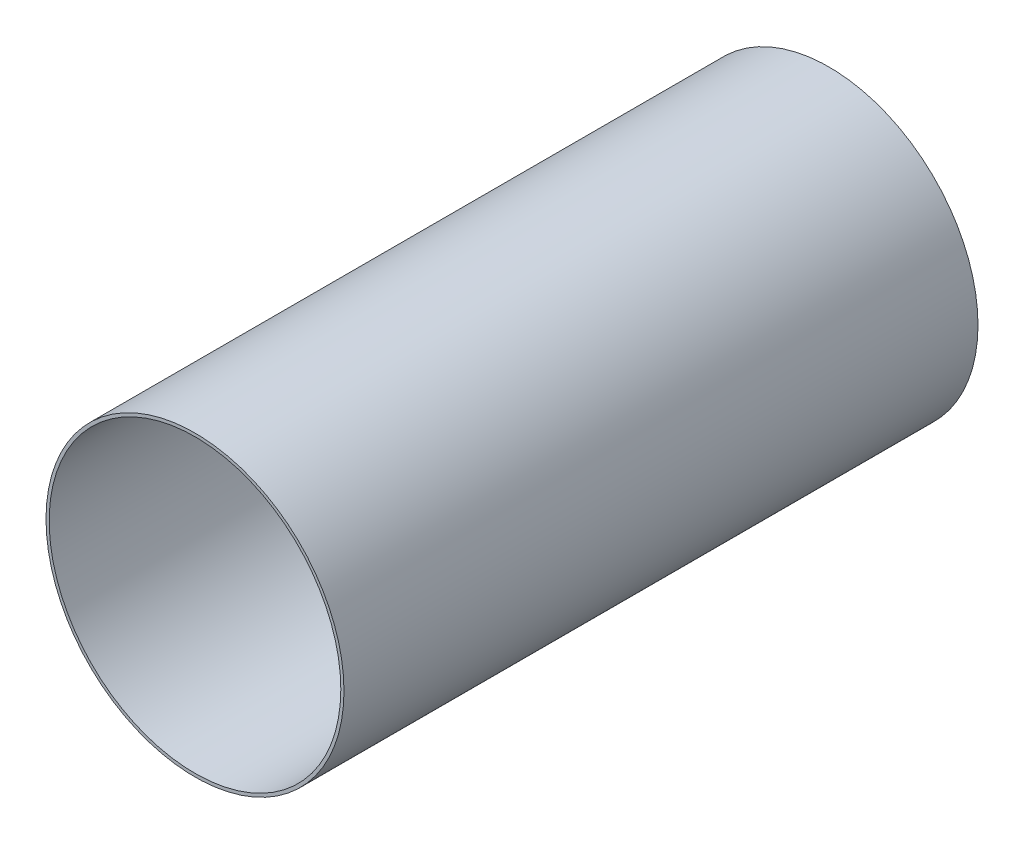
SolidWorks part; units mm, degrees
ref_plane "Alzado" through (0, 0, 0) normal (0, 0, 1) x (1, 0, 0)
ref_plane "Planta" through (0, 0, 0) normal (0, 1, 0) x (1, 0, 0)
ref_plane "Vista lateral" through (0, 0, 0) normal (1, 0, 0) x (0, 0, -1)
sketch "Croquis1" plane through (0, 0, 0) normal (0, 0, 1) x (1, 0, 0)
  circle A0 centre (0, 0) radius 23.5
  circle A1 centre (0, 0) radius 23
  dimension "D1" = 47
  dimension "D2" = 0.5
extrude "Saliente-Extruir1" add sketch "Croquis1" along normal blind 100
sketch "Croquis2" plane through (0, 0, 0) normal (0, 1, 0) x (1, 0, 0)
  line L0 (-23.5, -100) -> (23.5, -100) construction
  circle A0 centre (0, -85) radius 6
  dimension "D2" = 12
  dimension "D1" = 15
